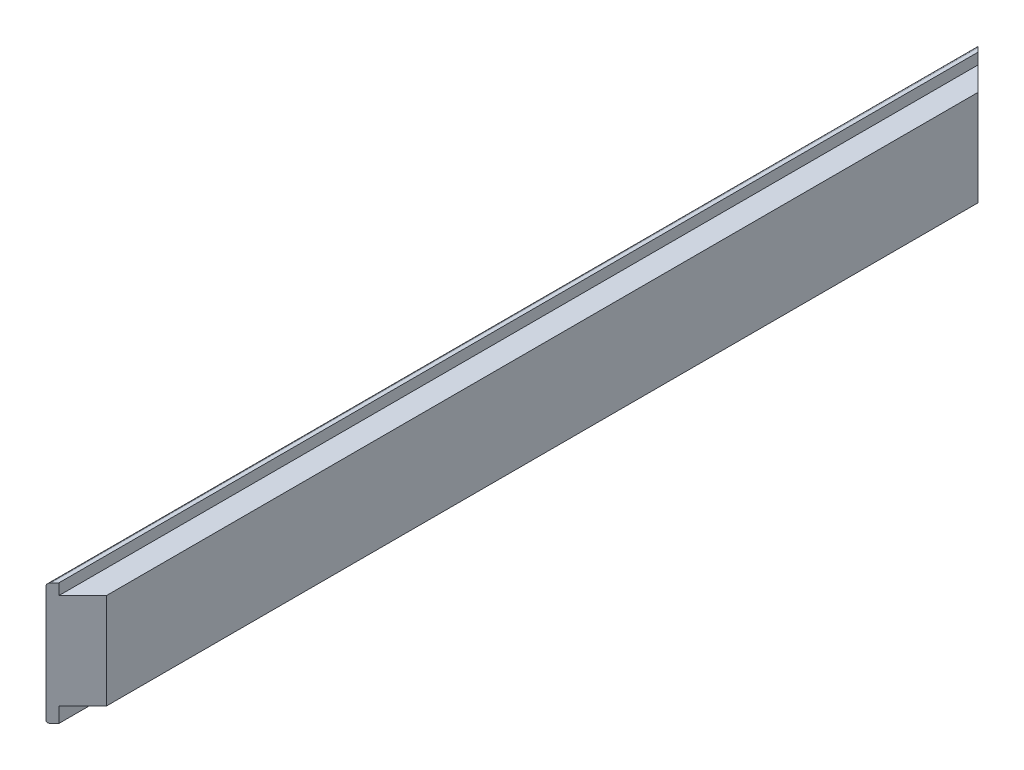
SolidWorks part; units mm, degrees
ref_plane "Front Plane" through (0, 0, 0) normal (0, 0, 1) x (1, 0, 0)
ref_plane "Top Plane" through (0, 0, 0) normal (0, 1, 0) x (1, 0, 0)
ref_plane "Right Plane" through (0, 0, 0) normal (1, 0, 0) x (0, 0, -1)
sketch "Sketch1" plane through (0, 0, 0) normal (0, 0, 1) x (1, 0, 0)
  line L1 (0, 0) -> (19.05, 0)
  line L2 (0, 0) -> (0, 77)
  line L3 (0, 77) -> (19.05, 77)
  line L4 (19.05, 0) -> (19.05, 77)
  line L5 (19.05, 77) -> (4.05, 77)
  line L6 (19.05, 77) -> (19.05, 70)
  line L7 (19.05, 70) -> (4.05, 70)
  line L8 (4.05, 77) -> (4.05, 70)
  line L9 (19.05, 0) -> (4.05, 0)
  line L10 (19.05, 0) -> (19.05, 9.525)
  line L11 (19.05, 9.525) -> (4.05, 9.525)
  line L12 (4.05, 0) -> (4.05, 9.525)
  dimension "D3" = 15
  dimension "D4" = 9.525
  dimension "D5" = 7
  dimension "D1" = 77
  dimension "D2" = 19.05
extrude "Boss-Extrude1" add sketch "Sketch1" along normal mid plane 589.1 contours L1 L12 L11 L4 L7 L8 L3 L2
fillet "Fillet1" radius 1.5875 2 edges at (0, 0, 0) (0, 77, 0)
sketch "Sketch2" plane through (0, 77, 0) normal (0, 1, 0) x (1, 0, 0)
  line L4 (0, 294.55) -> (19.05, 275.5)
  line L5 (19.05, 275.5) -> (19.05, 294.55)
  line L6 (19.05, 294.55) -> (0, 294.55)
  line L7 (-10.4775, 0) -> (10.4775, 0) construction
  line L9 (19.05, 275.5) -> (19.05, 294.55)
  line L13 (19.05, -294.55) -> (24.8228, -295)
  line L14 (19.05, -275.5) -> (19.05, -294.55)
  line L16 (19.05, -294.55) -> (0, -294.55)
  line L17 (19.05, -275.5) -> (19.05, -294.55)
  line L18 (0, -294.55) -> (19.05, -275.5)
  line L19 (19.05, -294.55) -> (19.05, 294.55) construction
extrude "Cut-Extrude1" cut sketch "Sketch2" against normal through all both and the other way through all
sketch "Sketch3" plane through (0, 9.525, 0) normal (0, -1, 0) x (1, 0, 0)
  line L0 (4.05, -260.5) -> (19.05, -260.5) construction
  line L1 (19.05, 275.5) -> (19.05, -275.5) construction
  line L2 (4.05, 290.5) -> (4.05, -290.5) construction
  line L3 (0, 0) -> (19.05, 0) construction
  line L4 (0, -294.55) -> (0, 294.55) construction
  line L5 (4.05, 260.5) -> (19.05, 260.5) construction
  point P0 (11.55, -260.5)
  point P6 (11.55, -260.5)
  point P10 (11.55, 260.5)
  dimension "D1" = 15
sketch "Sketch5" plane through (0, 0, 0) normal (0, 1, 0) x (1, 0, 0)
  line L0 (22.86, 294.55) -> (22.86, 219.55) construction
  line L1 (35.56, 294.55) -> (35.56, 219.55)
  line L2 (10.16, 294.55) -> (10.16, 219.55)
  line L5 (-10.4775, 0) -> (10.4775, 0) construction
  line L9 (19.05, -275.5) -> (19.05, 275.5) construction
  line L10 (22.86, -294.55) -> (22.86, -219.55) construction
  line L11 (35.56, -294.55) -> (35.56, -219.55)
  line L12 (10.16, -294.55) -> (10.16, -219.55)
  arc A0 (35.56, 294.55) -> (10.16, 294.55) centre (22.86, 294.55) ccw
  arc A1 (10.16, 219.55) -> (35.56, 219.55) centre (22.86, 219.55) ccw
  arc A4 (35.56, -294.55) -> (10.16, -294.55) centre (22.86, -294.55) cw
  arc A5 (10.16, -219.55) -> (35.56, -219.55) centre (22.86, -219.55) cw
  point P2 (22.86, 257.05)
  point P16 (22.86, -257.05)
  dimension "D1" = 25.4
  dimension "D2" = 75
  dimension "D3" = 3.81
extrude "Cut-Extrude2" [suppressed] cut sketch "Sketch5" along normal blind 25.4
sketch "Sketch6" plane through (0, 9.525, 0) normal (0, -1, 0) x (1, 0, 0)
  line L1 (10.4775, 0) -> (-10.4775, 0) construction
  line L7 (11.55, -283) -> (11.55, 73.9) construction
  line L8 (19.05, 275.5) -> (19.05, -275.5) construction
  line L9 (19.05, -275.5) -> (4.05, -290.5) construction
  point P4 (11.55, 104.55)
  point P14 (11.55, -104.55)
  dimension "D1" = 7.5
  dimension "D2" = 190
hole_wizard "Ø7.9 (7.9) Diameter Hole2" positions "Sketch6" profile "Sketch7" hole size "Ø7.9" standard "ISO"
sketch "Sketch7" plane through (11.55, 9.525, -104.55) normal (1, 0, 0) x (0, 0, -1)
  line L0 (0, 0) -> (0, 17.3734)
  line L1 (0, 17.3734) -> (3.95, 15)
  line L2 (3.95, 15) -> (3.95, 0)
  line L5 (3.95, 0) -> (0, 0)
  line L10 (0, 17.3734) -> (-3.95, 15) construction
  line L11 (0, -6.35) -> (0, 107.95) construction
  dimension "Hole Dia." = 7.9
  dimension "Hole Depth" = 15
  dimension "Drill Angle" = 118
sketch "Sketch8" plane through (0, 0, 0) normal (0, 0, 1) x (1, 0, 0)
  line L1 (0, 88.9) -> (19.05, 88.9)
  line L2 (0, 88.9) -> (0, 0)
  line L3 (0, 0) -> (19.05, 0)
  line L4 (19.05, 88.9) -> (19.05, 0)
  dimension "D1" = 19.05
  dimension "D2" = 88.9
equation "\"SquareSize\" = 5cm"
equation "\"TileCountX\"=12"
equation "\"TileCountY\"= 8"
equation "\"BottomBoardXSize\" = 880mm"
equation "\"BottomBoardYSize\" = 580mm"
equation "\"TopBoardXSize\" = 881mm"
equation "\"TopBoardYSize\"= 581mm"
equation "\"GantryHeight\"= 64mm"
equation "\"EncWallThickness\"= 5mm"
equation "\"EncLip\"= 15mm"
equation "\"TopBoardThickness\"= 3mm"
equation "\"BottomBoardThickness\"= .375in"
equation "\"D3@Sketch1\"=\"EncLip\""
equation "\"D4@Sketch1\"=\"BottomBoardThickness\""
equation "\"D5@Sketch1\"=7mm"
equation "\"D1@Boss-Extrude1\"=581mm+2*4.05000000mm"
equation "\"D1@Sketch6\"=\"EncLip\"/2"
equation "\"D1@Sketch1\"=\"GantryHeight\"+\"TopBoardThickness\"+10mm"
